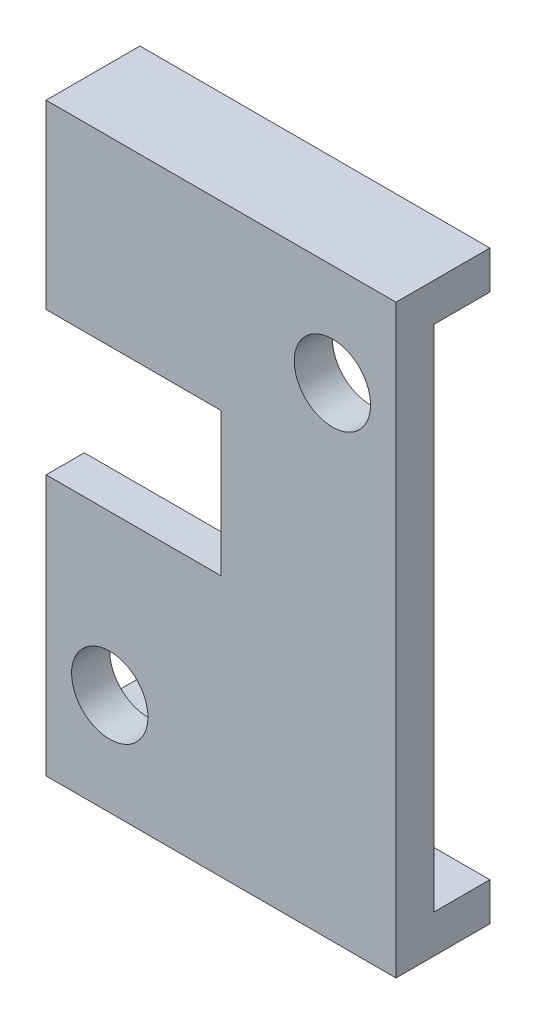
SolidWorks part; units mm, degrees
ref_plane "Front Plane" through (0, 0, 0) normal (0, 0, 1) x (1, 0, 0)
ref_plane "Top Plane" through (0, 0, 0) normal (0, 1, 0) x (1, 0, 0)
ref_plane "Right Plane" through (0, 0, 0) normal (1, 0, 0) x (0, 0, -1)
sketch "Sketch1" plane through (0, 0, 0) normal (1, 0, 0) x (0, 0, -1)
  line L0 (0, 0) -> (-2.95, 0)
  line L1 (-2.95, 0) -> (-2.95, 18.4)
  line L2 (-2.95, 18.4) -> (0, 18.4)
  line L3 (0, 18.4) -> (0, 17.2)
  line L4 (0, 17.2) -> (-1.75, 17.2)
  line L5 (-1.75, 17.2) -> (-1.75, 1.2)
  line L6 (-1.75, 1.2) -> (0, 1.2)
  line L7 (0, 1.2) -> (0, 0)
  dimension "D1" = 16
  dimension "D2" = 1.2
  dimension "D3" = 1.75
  dimension "D4" = 1.2
extrude "Boss-Extrude1" add sketch "Sketch1" along normal blind 11
sketch "Sketch3" plane through (0, 0, 1.75) normal (0, 0, -1) x (-1, 0, 0)
  line L0 (0, 1.2) -> (0, 17.2) construction
  line L1 (0, 12.7) -> (-5.5, 12.7)
  line L2 (0, 12.7) -> (0, 8.2)
  line L3 (0, 8.2) -> (-5.5, 8.2)
  line L4 (-5.5, 12.7) -> (-5.5, 8.2)
  line L5 (-11, 17.2) -> (0, 17.2) construction
  line L6 (-11, 1.2) -> (-11, 17.2) construction
  line L7 (-11, 1.2) -> (0, 1.2) construction
  circle A0 centre (-9, 15.2) radius 1.2
  circle A1 centre (-2, 3.2) radius 1.2
  dimension "D1" = 2.4
  dimension "D2" = 2
  dimension "D3" = 2
  dimension "D4" = 2
  dimension "D5" = 2
  dimension "D6" = 4.5
  dimension "D7" = 7
  dimension "D8" = 5.5
extrude "Cut-Extrude1" cut sketch "Sketch3" against normal through all
equation "\"BoardLength\"= 11"
equation "\"BoardHeight\"= 16"
equation "\"BoardThickness\"= 0.4"
equation "\"ScrewHoleDiameter\"= 2.4"
equation "\"PrintThickness\"= 1.2"
equation "\"D1@Sketch1\"=\"BoardHeight\""
equation "\"D2@Sketch1\"=\"PrintThickness\""
equation "\"D3@Sketch1\"=\"BoardThickness\"+\"PrintThickness\"+0.15"
equation "\"D4@Sketch1\"=\"PrintThickness\""
equation "\"D1@Boss-Extrude1\"=\"BoardLength\""
equation "\"D1@Sketch3\"=\"ScrewHoleDiameter\""
